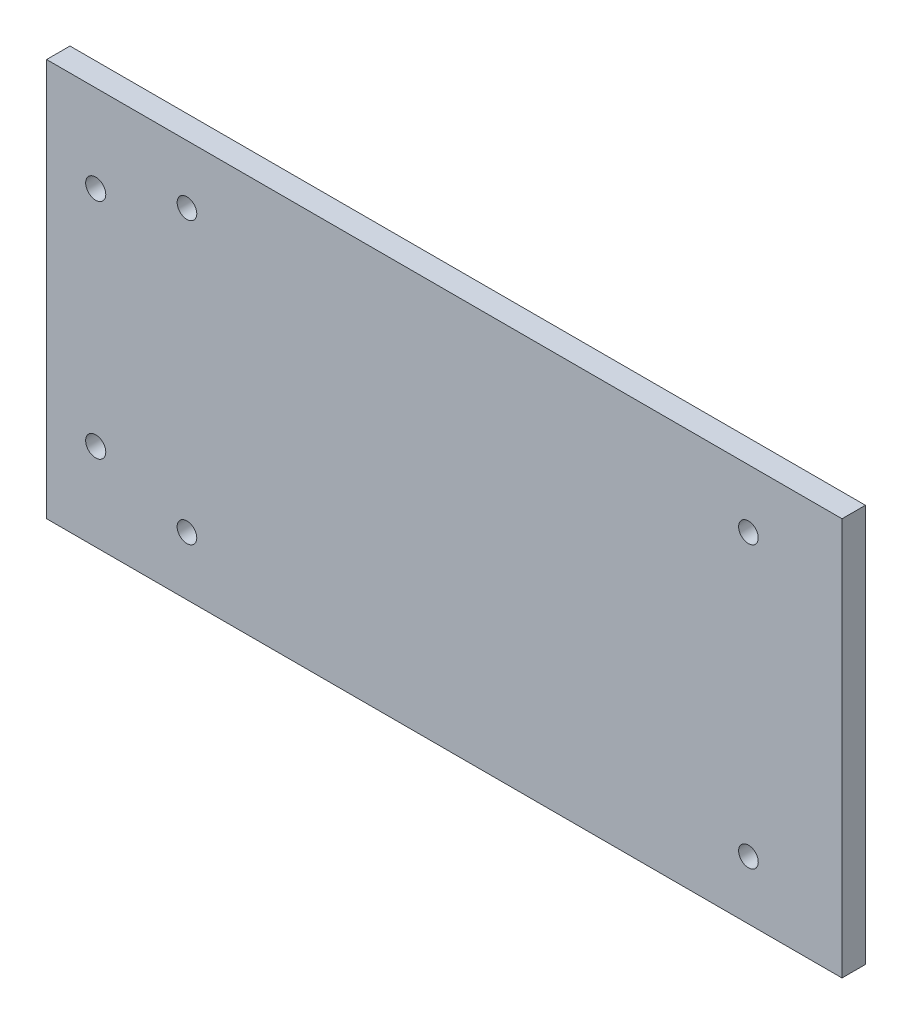
SolidWorks part; units mm, degrees
ref_plane "Front Plane" through (0, 0, 0) normal (1, 0, 0) x (0, 1, 0)
ref_plane "Top Plane" through (0, 0, 0) normal (0, 0, 1) x (0, 1, 0)
ref_plane "Right Plane" through (0, 0, 0) normal (0, 1, 0) x (-1, 0, 0)
sketch "Sketch1" plane through (0, 0, 0) normal (0, 0, 1) x (0, 1, 0)
  line L0 (0, -1000) -> (0, 49000) construction
  line L1 (-42.5, -85) -> (42.5, -85)
  line L2 (-42.5, -85) -> (-42.5, 85)
  line L3 (-42.5, 85) -> (42.5, 85)
  line L4 (42.5, -85) -> (42.5, 85)
  line L5 (-42.5, -85) -> (42.5, 85) construction
  line L6 (-42.5, 85) -> (42.5, -85) construction
  line L7 (-1000, 0) -> (49000, 0) construction
  circle A0 centre (-30, 55) radius 2.1
  circle A1 centre (-30, -65) radius 2.1
  circle A2 centre (30, -65) radius 2.1
  circle A3 centre (30, 55) radius 2.1
  point P0 (0, 0)
  dimension "D5" = 4.2
  dimension "D8" = 4.2
  dimension "D1" = 85
  dimension "D2" = 170
  dimension "D3" = 30
  dimension "D4" = 30
  dimension "D6" = 120
  dimension "D7" = 30
extrude "Boss-Extrude1" add sketch "Sketch1" along normal blind 5
sketch "Sketch2" plane through (0, 0, 5) normal (0, 0, 1) x (0, -1, 0)
  line L0 (42.5, -85) -> (42.5, 85) construction
  line L1 (-42.5, -85) -> (42.5, -85) construction
  circle A0 centre (23.85, -74.5) radius 2.15
  dimension "D1" = 4.3
  dimension "D2" = 18.65
  dimension "D3" = 10.5
extrude "Cut-Extrude1" cut sketch "Sketch2" against normal blind 10
sketch "Sketch3" plane through (0, 0, 5) normal (0, 0, 1) x (0, -1, 0)
  line L0 (-42.5, -85) -> (42.5, -85) construction
  line L1 (-42.5, 85) -> (-42.5, -85) construction
  circle A0 centre (-23.85, -74.5) radius 2.15
  dimension "D1" = 4.3
  dimension "D2" = 10.5
  dimension "D3" = 18.65
extrude "Cut-Extrude2" cut sketch "Sketch3" against normal blind 10
